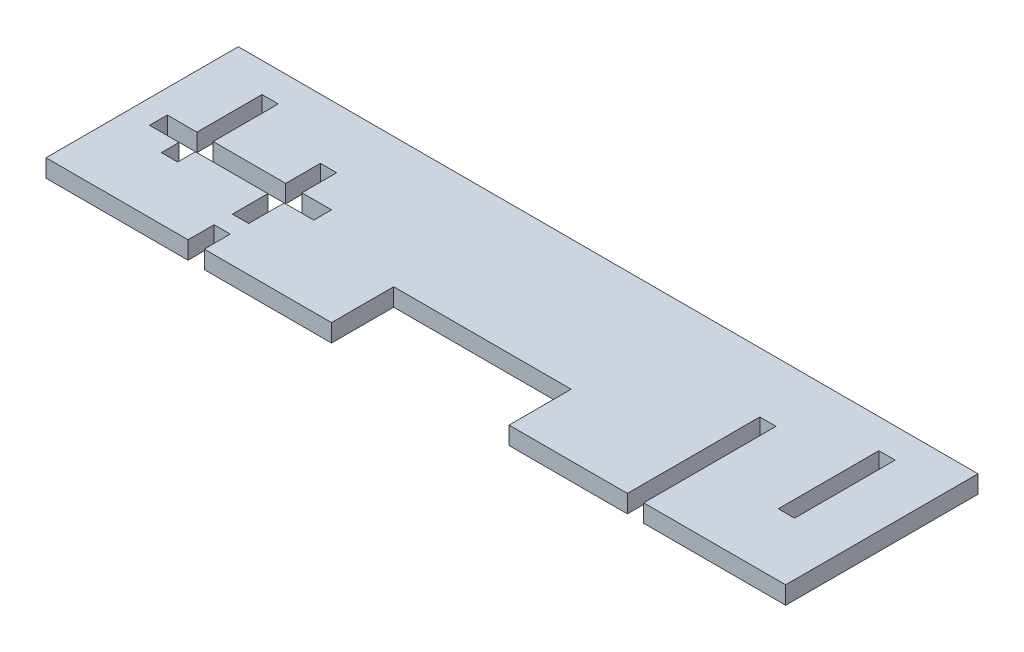
SolidWorks part; units mm, degrees
ref_plane "Front" through (0, 0, 0) normal (0, 0, 1) x (1, 0, 0)
ref_plane "Top" through (0, 0, 0) normal (0, 1, 0) x (1, 0, 0)
ref_plane "Right" through (0, 0, 0) normal (1, 0, 0) x (0, 0, -1)
sketch "Sketch1" plane through (0, 0, 0) normal (0, 1, 0) x (1, 0, 0)
  line L1 (0, 0) -> (250, 0)
  line L2 (0, 0) -> (0, 65)
  line L3 (0, 65) -> (250, 65)
  line L4 (250, 0) -> (250, 65)
  point P4 (0, 0)
  dimension "D1" = 65
  dimension "D2" = 250
extrude "Boss-Extrude1" add sketch "Sketch1" along normal blind 6
sketch "Sketch2" plane through (0, 6, 0) normal (0, 1, 0) x (1, 0, 0)
  line L0 (125, 65) -> (125, 0) construction
  line L1 (18, 55) -> (23.5, 55)
  line L2 (18, 55) -> (18, 21)
  line L3 (18, 21) -> (23.5, 21)
  line L4 (23.5, 55) -> (23.5, 21)
  line L5 (48, 44.75) -> (53.5, 44.75)
  line L6 (48, 44.75) -> (48, -2.75)
  line L7 (48, -2.75) -> (53.5, -2.75)
  line L8 (53.5, 44.75) -> (53.5, -2.75)
  line L9 (250, 65) -> (0, 65) construction
  line L10 (0, 0) -> (250, 0) construction
  line L11 (0, 32.5) -> (125, 32.5) construction
  line L12 (0, 65) -> (0, 0) construction
  line L13 (196.5, 44.75) -> (196.5, -2.75)
  line L14 (202, -2.75) -> (196.5, -2.75)
  line L15 (202, 44.75) -> (202, -2.75)
  line L16 (202, 44.75) -> (196.5, 44.75)
  line L17 (226.5, 55) -> (226.5, 21)
  line L18 (232, 21) -> (226.5, 21)
  line L19 (232, 55) -> (232, 21)
  line L20 (232, 55) -> (226.5, 55)
  point P14 (18, 38)
  dimension "D1" = 107
  dimension "D2" = 24.5
  dimension "D3" = 47.5
  dimension "D4" = 34
  dimension "D5" = 5.5
  dimension "D6" = 10.25
  dimension "D7" = 10
extrude "Cut-Extrude1" cut sketch "Sketch2" against normal through all
sketch "Sketch3" plane through (0, 6, 0) normal (0, 1, 0) x (1, 0, 0)
  line L0 (0, 0) -> (48, 0) construction
  line L1 (156.5, 0) -> (96.5, 0)
  line L2 (156.5, 0) -> (156.5, 21)
  line L3 (156.5, 21) -> (96.5, 21)
  line L4 (96.5, 0) -> (96.5, 21)
  line L5 (196.5, 44.75) -> (196.5, 0) construction
  line L6 (18, 21) -> (23.5, 21) construction
  dimension "D1" = 40
  dimension "D2" = 60
extrude "Cut-Extrude2" cut sketch "Sketch3" against normal through all
sketch "Sketch4" plane through (0, 6, 0) normal (0, 1, 0) x (1, 0, 0)
  line L1 (8, 33) -> (63.5, 33)
  line L2 (8, 33) -> (8, 27)
  line L3 (8, 27) -> (63.5, 27)
  line L4 (63.5, 33) -> (63.5, 27)
  line L6 (18, 21) -> (23.5, 21) construction
  line L7 (53.5, 0) -> (53.5, 44.75) construction
  line L8 (18, 55) -> (18, 21) construction
  dimension "D1" = 6
  dimension "D2" = 6
  dimension "D3" = 10
  dimension "D4" = 10
extrude "Cut-Extrude3" cut sketch "Sketch4" against normal through all
sketch "Sketch5" plane through (0, 6, 0) normal (0, 1, 0) x (1, 0, 0)
  line L0 (48, 27) -> (48, 0) construction
  line L1 (48, 15) -> (53.5, 15)
  line L2 (48, 15) -> (48, 8.8)
  line L3 (48, 8.8) -> (53.5, 8.8)
  line L4 (53.5, 15) -> (53.5, 8.8)
  line L5 (53.5, 0) -> (53.5, 27) construction
  line L6 (53.5, 27) -> (63.5, 27) construction
  dimension "D1" = 6.2
  dimension "D2" = 12
extrude "Boss-Extrude2" add sketch "Sketch5" against normal blind 6
